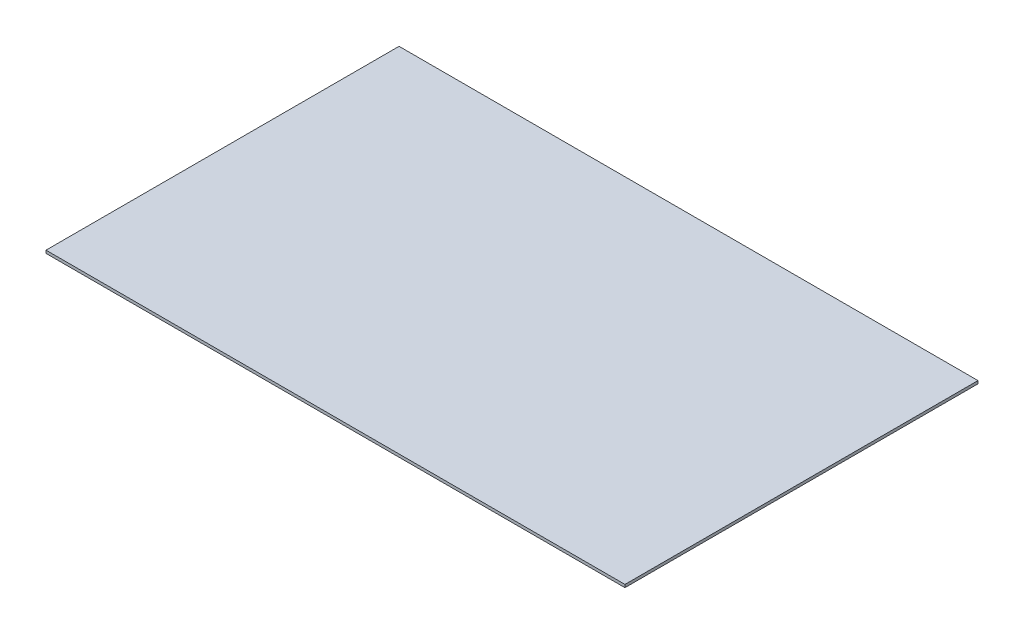
SolidWorks part; units mm, degrees
material "Mahogany"
ref_plane "Front Plane" through (0, 0, 0) normal (0, 0, 1) x (1, 0, 0)
ref_plane "Top Plane" through (0, 0, 0) normal (0, 1, 0) x (1, 0, 0)
ref_plane "Right Plane" through (0, 0, 0) normal (1, 0, 0) x (0, 0, -1)
sketch "Sketch1" plane through (0, 0, 0) normal (0, 1, 0) x (1, 0, 0)
  line L1 (-255, -155.5) -> (255, -155.5)
  line L2 (-255, -155.5) -> (-255, 155.5)
  line L3 (-255, 155.5) -> (255, 155.5)
  line L4 (255, -155.5) -> (255, 155.5)
  line L5 (-255, -155.5) -> (255, 155.5) construction
  line L6 (-255, 155.5) -> (255, -155.5) construction
  point P0 (0, 0)
  dimension "D1" = 510
  dimension "D2" = 311
extrude "Boss-Extrude1" add sketch "Sketch1" along normal mid plane 2.5
